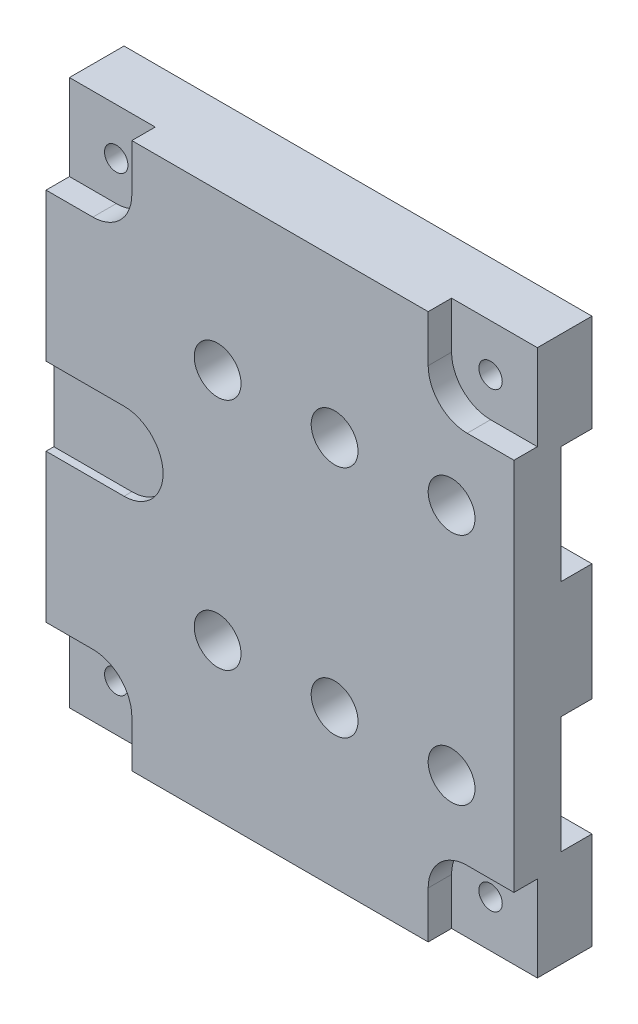
SolidWorks part; units mm, degrees
ref_plane "前视基准面" through (0, 0, 0) normal (0, 0, 1) x (1, 0, 0)
ref_plane "上视基准面" through (0, 0, 0) normal (0, 1, 0) x (1, 0, 0)
ref_plane "右视基准面" through (0, 0, 0) normal (1, 0, 0) x (0, 0, -1)
sketch "草图1" plane through (0, 0, 0) normal (0, 0, 1) x (1, 0, 0)
  line L1 (-30, 35) -> (30, 35)
  line L2 (-30, 35) -> (-30, -35)
  line L3 (-30, -35) -> (30, -35)
  line L4 (30, 35) -> (30, -35)
  line L5 (-30, 35) -> (30, -35) construction
  line L6 (-30, -35) -> (30, 35) construction
  point P0 (0, 0)
  dimension "D1" = 60
  dimension "D2" = 70
extrude "凸台-拉伸1" add sketch "草图1" along normal blind 10
sketch "草图2" plane through (0, 0, 10) normal (0, 0, 1) x (1, 0, 0)
  line L0 (0, 0) -> (24.7398, 0) construction
  line L1 (0, 15) -> (30, 15) construction
  line L3 (5.5, 0) -> (-5.5, 0) construction
  line L4 (-2.1573, -15) -> (27.8427, -15) construction
  circle A0 centre (-8, 15) radius 3
  circle A1 centre (7, 15) radius 3
  circle A2 centre (-8, -15) radius 3
  circle A3 centre (7, -15) radius 3
  circle A6 centre (22, 15) radius 3
  circle A7 centre (22, -15) radius 3
  dimension "D6" = 6
  dimension "D7" = 6
  dimension "D8" = 6
  dimension "D9" = 6
  dimension "D14" = 6
  dimension "D15" = 6
  dimension "D1" = 15
  dimension "D2" = 15
  dimension "D3" = 15
  dimension "D12" = 15
  dimension "D13" = 15
extrude "切除-拉伸1" cut sketch "草图2" against normal through all
sketch "草图3" plane through (0, 0, 0) normal (0, 0, -1) x (-1, 0, 0)
  line L0 (8, 22.5) -> (-30, 22.5)
  line L1 (8, 7.5) -> (-30, 7.5)
  line L4 (-30, 35) -> (-30, -35)
  line L5 (-30, -35) -> (30, -35)
  line L6 (30, -35) -> (30, 35)
  line L7 (30, 35) -> (-30, 35)
  line L8 (-30, 35) -> (-30, -35)
  line L9 (-30, -35) -> (30, -35)
  line L10 (30, -35) -> (30, 35)
  line L11 (30, 35) -> (-30, 35)
  circle A0 centre (8, -15) radius 3 construction
  circle A1 centre (-7, -15) radius 3 construction
  circle A2 centre (8, 15) radius 3 construction
  circle A3 centre (-7, 15) radius 3 construction
  circle A4 centre (8, -15) radius 3
  circle A5 centre (-7, -15) radius 3
  circle A6 centre (8, 15) radius 3
  circle A7 centre (-7, 15) radius 3
  circle A8 centre (8, 15) radius 7.5
  circle M7 centre (-7, 15) radius 3
  circle M10 centre (8, 15) radius 3
  line M11 (-30, 35) -> (-30, -35)
  dimension "D2" = 15
  dimension "D1" = 0
extrude "切除-拉伸2" cut sketch "草图3" against normal blind 4 contours A8 M10 | A8 L0 L1 M11 M7
mirror "镜向1" about plane through (0, 0, 0) normal (0, 1, 0) of "切除-拉伸2"
sketch "草图4" plane through (0, 0, 10) normal (0, 0, 1) x (1, 0, 0)
  line L0 (-20, 5) -> (-30, 5)
  line L1 (-20, -5) -> (-30, -5)
  line L4 (30, -35) -> (30, 35)
  line L5 (30, 35) -> (-30, 35)
  line L6 (-30, 35) -> (-30, -35)
  line L7 (-30, -35) -> (30, -35)
  line L8 (30, -35) -> (30, 35)
  line L9 (30, 35) -> (-30, 35)
  line L10 (-30, 35) -> (-30, -35)
  line L11 (-30, -35) -> (30, -35)
  circle A0 centre (-20, 0) radius 5
  line M14 (-30, 35) -> (-30, -35)
  dimension "D2" = 10
  dimension "D3" = 10
  dimension "D1" = 0
extrude "切除-拉伸3" cut sketch "草图4" against normal blind 1 contours A0 | A0 L0 L1 M14
sketch "草图6" plane through (0, 35, 0) normal (0, 1, 0) x (1, 0, 0)
  line L0 (0, -5.5) -> (0, 5.5) construction
  line L4 (30, 0) -> (-30, 0)
  line L5 (-30, 0) -> (-30, -10)
  line L6 (-30, -10) -> (30, -10)
  line L7 (30, -10) -> (30, 0)
  line L8 (30, 0) -> (-30, 0)
  line L9 (-30, 0) -> (-30, -10)
  line L10 (-30, -10) -> (30, -10)
  line L11 (30, -10) -> (30, 0)
  arc A0 (-30, 0) -> (-17, 13) centre (-30, 13) ccw
  arc A1 (-17, 13) -> (17, 13) centre (0, 13) cw
  arc A2 (30, 0) -> (17, 13) centre (30, 13) cw
  point P8 (0, 0)
  line M5 (30, 0) -> (-30, 0)
  dimension "D2" = 13
  dimension "D1" = 0
extrude "凸台-拉伸2" add sketch "草图6" against normal blind 12.5 contours A2 A1 A0 M5
sketch "草图7" plane through (0, 35, 0) normal (0, 1, 0) x (1, 0, 0)
  line L0 (0, 22.5) -> (0, 30) construction
  line L1 (-5, 29.2481) -> (-5, 21.0777)
  line L2 (5, 29.2481) -> (5, 21.0777)
  line L3 (30, -10) -> (30, 0)
  line L4 (-30, 0) -> (-30, -10)
  line L5 (-30, -10) -> (30, -10)
  line L6 (30, -10) -> (30, 0)
  line L7 (-30, 0) -> (-30, -10)
  line L8 (-30, -10) -> (30, -10)
  circle A0 centre (0, 13) radius 9.5
  arc A3 (17, 13) -> (30, 0) centre (30, 13) ccw
  arc A4 (17, 13) -> (-17, 13) centre (0, 13) ccw
  arc A5 (-30, 0) -> (-17, 13) centre (-30, 13) ccw
  arc A6 (17, 13) -> (30, 0) centre (30, 13) ccw
  arc A7 (17, 13) -> (-17, 13) centre (0, 13) ccw
  arc A8 (-30, 0) -> (-17, 13) centre (-30, 13) ccw
  dimension "D2" = 19
  dimension "D3" = 5
  dimension "D1" = 0
extrude "切除-拉伸4" cut sketch "草图7" against normal up to surface (12.5 mm away) contours A0 up to face at (2, 22.5, -4.2307)
mirror "镜向2" about plane through (0, 0, 0) normal (0, 1, 0) of "切除-拉伸4", "凸台-拉伸2"
sketch "草图8" plane through (0, 0, 0) normal (0, 0, -1) x (-1, 0, 0)
  line L7 (30, -5) -> (20, -5)
  line L8 (30, -35) -> (30, -5)
  line L9 (-30, -35) -> (30, -35)
  line L10 (-30, 35) -> (-30, -35)
  line L11 (30, 35) -> (-30, 35)
  line L12 (30, 5) -> (30, 35)
  line L13 (20, 5) -> (30, 5)
  line L14 (30, -5) -> (20, -5)
  line L15 (30, -35) -> (30, -5)
  line L16 (-30, -35) -> (30, -35)
  line L17 (-30, 35) -> (-30, -35)
  line L18 (30, 35) -> (-30, 35)
  line L19 (30, 5) -> (30, 35)
  line L20 (20, 5) -> (30, 5)
  arc A1 (20, 5) -> (20, -5) centre (20, 0) ccw
  arc A2 (20, 5) -> (20, -5) centre (20, 0) ccw
  dimension "D1" = 0
extrude "切除-拉伸5" cut sketch "草图8" along normal through all
sketch "草图9" plane through (0, 0, 0) normal (0, 0, -1) x (-1, 0, 0)
  line L10 (-30, -35) -> (30, -35)
  line L11 (30, -35) -> (30, 35)
  line L12 (30, 35) -> (-30, 35)
  line L13 (-30, 35) -> (-30, 22.5)
  line L14 (-30, 22.5) -> (8, 22.5)
  line L15 (8, 7.5) -> (-30, 7.5)
  line L16 (-30, 7.5) -> (-30, -7.5)
  line L17 (-30, -7.5) -> (8, -7.5)
  line L18 (8, -22.5) -> (-30, -22.5)
  line L19 (-30, -22.5) -> (-30, -35)
  line L20 (-30, -35) -> (30, -35)
  line L21 (30, -35) -> (30, 35)
  line L22 (30, 35) -> (-30, 35)
  line L23 (-30, 35) -> (-30, 22.5)
  line L24 (-30, 22.5) -> (8, 22.5)
  line L25 (8, 7.5) -> (-30, 7.5)
  line L26 (-30, 7.5) -> (-30, -7.5)
  line L27 (-30, -7.5) -> (8, -7.5)
  line L28 (8, -22.5) -> (-30, -22.5)
  line L29 (-30, -22.5) -> (-30, -35)
  circle A0 centre (-24, -29) radius 1.5
  circle A1 centre (24, -29) radius 1.5
  arc A3 (8, 7.5) -> (8, 22.5) centre (8, 15) ccw
  arc A4 (8, -22.5) -> (8, -7.5) centre (8, -15) ccw
  arc A5 (8, 7.5) -> (8, 22.5) centre (8, 15) ccw
  arc A6 (8, -22.5) -> (8, -7.5) centre (8, -15) ccw
  dimension "D4" = 3
  dimension "D6" = 3
  dimension "D2" = 6
  dimension "D3" = 6
  dimension "D5" = 6
  dimension "D1" = 0
extrude "切除-拉伸6" cut sketch "草图9" against normal through all contours A0 | A1
sketch "草图10" plane through (0, 0, 10) normal (0, 0, 1) x (1, 0, 0)
  line L1 (-24, -24) -> (-30, -24)
  line L2 (-30, -5) -> (-30, -35) construction
  line L3 (-30, -24) -> (-30, -35)
  line L4 (-30, -35) -> (-19, -35)
  line L6 (-30, -35) -> (30, -35) construction
  line L7 (-19, -35) -> (-19, -29)
  line L8 (19, -29) -> (19, -35)
  line L9 (19, -35) -> (30, -35)
  line L10 (30, -35) -> (30, -24)
  line L11 (30, -35) -> (30, 35) construction
  line L12 (30, -24) -> (24, -24)
  circle A0 centre (24, -29) radius 1.5 construction
  circle A1 centre (-24, -29) radius 1.5 construction
  circle A3 centre (-24, -29) radius 1.5
  arc A5 (24, -24) -> (19, -29) centre (24, -29) ccw
  arc A6 (-19, -29) -> (-24, -24) centre (-24, -29) ccw
  circle A7 centre (24, -29) radius 1.5
  dimension "D1" = 10
  dimension "D2" = 10
extrude "切除-拉伸7" cut sketch "草图10" against normal blind 3
mirror "镜向3" about plane through (0, 0, 0) normal (0, 1, 0) of "切除-拉伸7", "切除-拉伸6"
